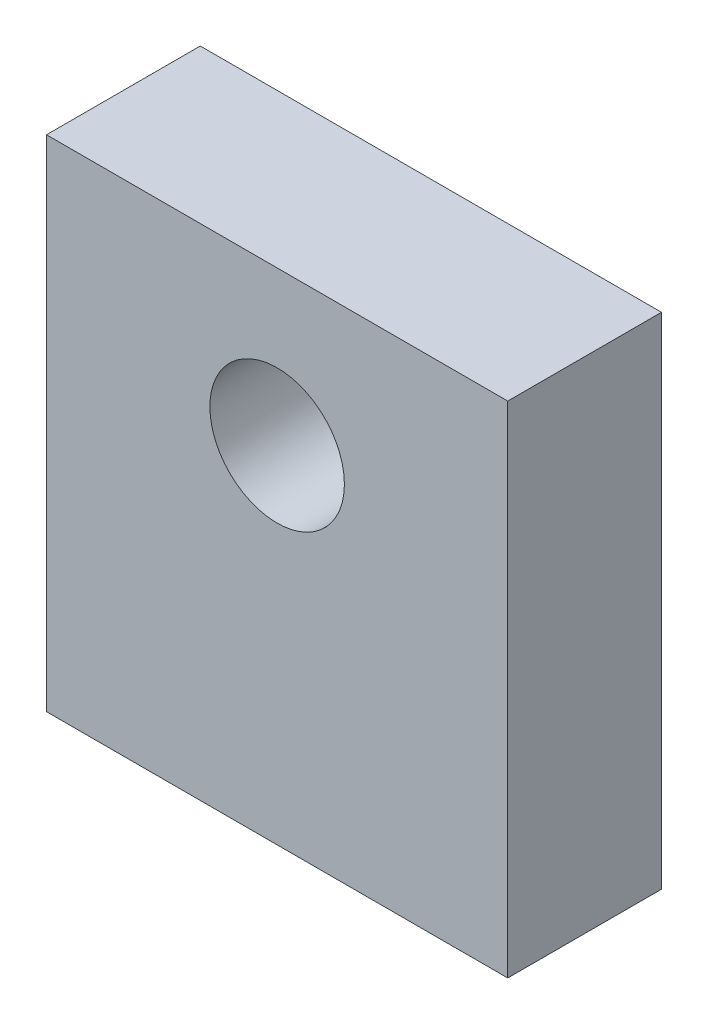
SolidWorks part; units mm, degrees
ref_plane "Front Plane" through (0, 0, 0) normal (0, 0, 1) x (1, 0, 0)
ref_plane "Top Plane" through (0, 0, 0) normal (0, 1, 0) x (1, 0, 0)
ref_plane "Right Plane" through (0, 0, 0) normal (1, 0, 0) x (0, 0, -1)
sketch "Sketch1" plane through (0, 0, 0) normal (0, 0, 1) x (1, 0, 0)
  line L0 (0, 0) -> (0, 41.275) construction
  line L1 (19.05, 0) -> (-19.05, 0)
  line L2 (19.05, 0) -> (19.05, 41.275)
  line L3 (19.05, 41.275) -> (-19.05, 41.275)
  line L4 (-19.05, 0) -> (-19.05, 41.275)
  circle A0 centre (0, 28.575) radius 5.5562
  dimension "D3" = 11.1125
  dimension "D1" = 38.1
  dimension "D2" = 41.275
  dimension "D4" = 28.575
extrude "Boss-Extrude1" add sketch "Sketch1" along normal blind 12.7
hole_wizard "#10-32 Tapped Hole1" positions "Sketch3" profile "Sketch2" tap size "#10-32" standard "ANSI Inch"
sketch "Sketch3" plane through (0, 0, 0) normal (0, -1, 0) x (-1, 0, 0)
  line L1 (-19.05, -12.7) -> (-19.05, 0) construction
  line L2 (19.05, 0) -> (-19.05, 0) construction
  point P0 (-13.97, -6.35)
  point P2 (13.97, -6.35)
  point P12 (-19.05, -6.35)
  dimension "D1" = 5.08
  dimension "D2" = 33.02
  dimension "D3" = 6.35
sketch "Sketch2" plane through (13.97, 0, 6.35) normal (1, 0, 0) x (0, 0, -1)
  line L0 (0, 0) -> (0, 17.0883)
  line L1 (0, 17.0883) -> (2.0193, 15.875)
  line L2 (2.0193, 15.875) -> (2.0193, 0)
  line L5 (2.0193, 0) -> (0, 0)
  line L10 (0, 17.0883) -> (-2.0193, 15.875) construction
  line L11 (0, -6.35) -> (0, 107.95) construction
  dimension "Tap Drill Dia." = 4.0386
  dimension "Tap Drill Depth" = 15.875
  dimension "Drill Angle" = 118
cosmetic thread "Hole Thread1"
cosmetic thread "Hole Thread2"
